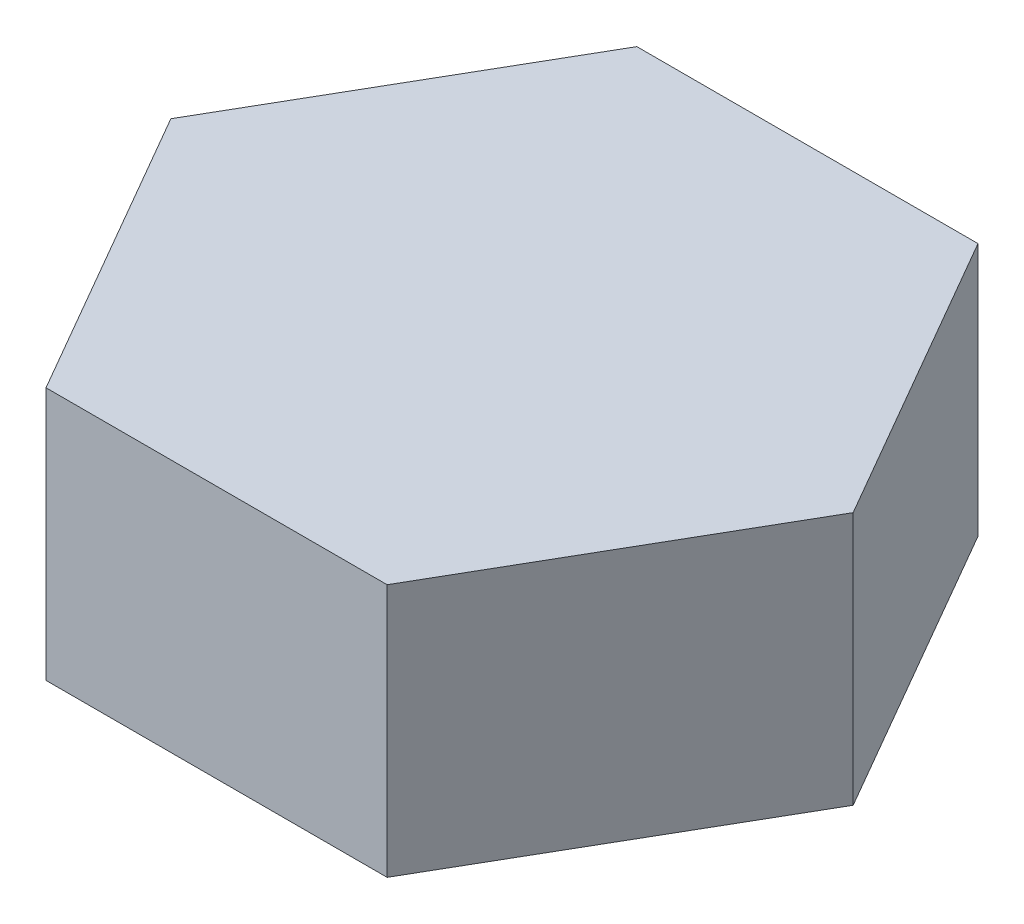
SolidWorks part; units mm, degrees
ref_plane "Front Plane" through (0, 0, 0) normal (0, 0, 1) x (1, 0, 0)
ref_plane "Top Plane" through (0, 0, 0) normal (0, 1, 0) x (1, 0, 0)
ref_plane "Right Plane" through (0, 0, 0) normal (1, 0, 0) x (0, 0, -1)
sketch "Sketch1" plane through (0, 0, 0) normal (0, 1, 0) x (1, 0, 0)
  line L1 (-40.3799, 0) -> (-20.1899, -34.97)
  line L2 (-20.1899, -34.97) -> (20.1899, -34.97)
  line L3 (20.1899, -34.97) -> (40.3799, 0)
  line L4 (40.3799, 0) -> (20.1899, 34.97)
  line L5 (20.1899, 34.97) -> (-20.1899, 34.97)
  line L6 (-20.1899, 34.97) -> (-40.3799, 0)
  circle A0 centre (0, 0) radius 34.97 construction
  dimension "D1" = 69.94
extrude "Boss-Extrude1" add sketch "Sketch1" along normal blind 30
